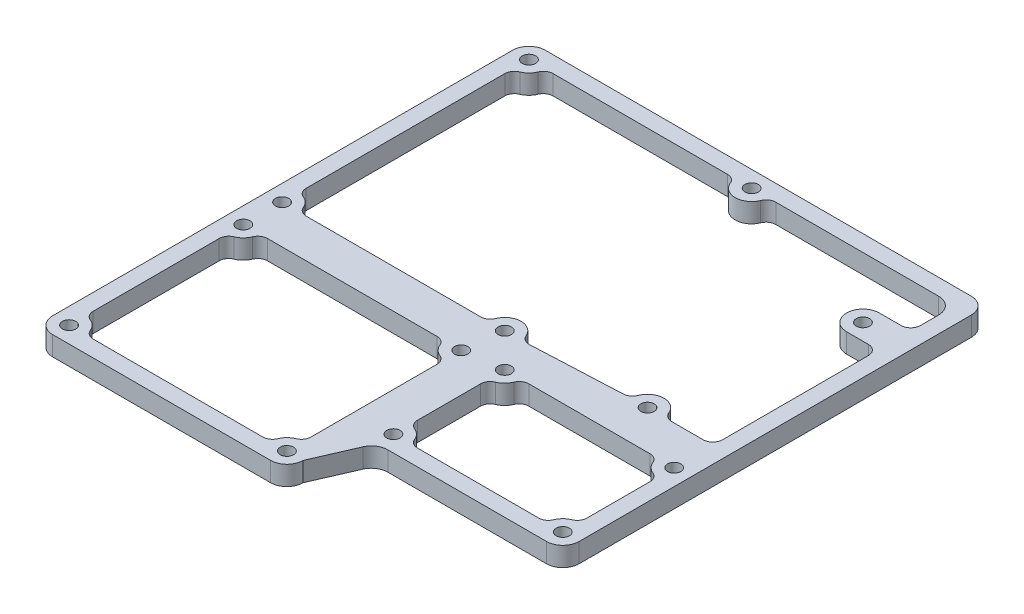
SolidWorks part; units mm, degrees
ref_plane "Front Plane" through (0, 0, 0) normal (0, 0, 1) x (1, 0, 0)
ref_plane "Top Plane" through (0, 0, 0) normal (0, 1, 0) x (1, 0, 0)
ref_plane "Right Plane" through (0, 0, 0) normal (1, 0, 0) x (0, 0, -1)
sketch "Sketch2" plane through (0, 0, 0) normal (0, 1, 0) x (1, 0, 0)
  line L1 (-46, 51) -> (0, 51) construction
  line L2 (-46, 51) -> (-46, 0) construction
  line L3 (-46, 0) -> (0, 0) construction
  line L4 (0, 51) -> (0, 0) construction
  line L5 (-46, -8) -> (-1, -8) construction
  line L6 (-46, -8) -> (-46, -44) construction
  line L7 (-46, -44) -> (-1, -44) construction
  line L8 (-1, -8) -> (-1, -44) construction
  line L9 (6, 52) -> (44, 52) construction
  line L10 (6, 52) -> (6, -2) construction
  line L11 (6, -2) -> (44, -2) construction
  line L12 (44, 52) -> (44, -2) construction
  line L13 (7, -7) -> (42, -7) construction
  line L14 (7, -7) -> (7, -30) construction
  line L15 (7, -30) -> (42, -30) construction
  line L16 (42, -7) -> (42, -30) construction
  circle A0 centre (-46, 51) radius 1.375
  circle A1 centre (0, 51) radius 1.375
  circle A2 centre (0, 0) radius 1.375
  circle A3 centre (-46, 0) radius 1.375
  circle A4 centre (-46, -8) radius 1.375
  circle A5 centre (-1, -8) radius 1.375
  circle A6 centre (-1, -44) radius 1.375
  circle A7 centre (-46, -44) radius 1.375
  circle A8 centre (28.5, 1) radius 1.375
  circle A9 centre (35.5, 38.5) radius 1.375
  circle A10 centre (7, -7) radius 1.375
  circle A11 centre (42, -7) radius 1.375
  circle A12 centre (42, -30) radius 1.375
  circle A13 centre (7, -30) radius 1.375
  circle A14 centre (-46, 51) radius 3.375
  circle A15 centre (0, 51) radius 3.375
  circle A16 centre (0, 0) radius 3.375
  circle A17 centre (-46, 0) radius 3.375
  circle A18 centre (-46, -8) radius 3.375
  circle A19 centre (-1, -8) radius 3.375
  circle A20 centre (7, -7) radius 3.375
  circle A21 centre (28.5, 1) radius 3.375
  circle A22 centre (35.5, 38.5) radius 3.375
  circle A23 centre (-1, -44) radius 3.375
  circle A24 centre (-46, -44) radius 3.375
  circle A25 centre (7, -30) radius 3.375
  circle A26 centre (42, -30) radius 3.375
  circle A27 centre (42, -7) radius 3.375
  point P33 (7.6139, -7)
  dimension "D3" = 2.75
  dimension "D4" = 45
  dimension "D9" = 3
  dimension "D17" = 5
  dimension "D1" = 46
  dimension "D2" = 51
  dimension "D5" = 36
  dimension "D6" = 8
  dimension "D7" = 38
  dimension "D8" = 54
  dimension "D10" = 15.5
  dimension "D11" = 13.5
  dimension "D12" = 8.5
  dimension "D13" = 2
  dimension "D14" = 6
  dimension "D15" = 35
  dimension "D16" = 23
  dimension "D18" = 2
  dimension "D19" = 2
extrude "Part screwholes" add sketch "Sketch2" along normal blind 4
sketch "Sketch3" plane through (0, 4, 0) normal (0, 1, 0) x (1, 0, 0)
  line L0 (-49.375, 51) -> (-49.375, -44)
  line L1 (-46, -47.375) -> (-1, -47.375)
  line L2 (2.375, -44) -> (6.1172, -35.403)
  line L3 (9.2118, -33.375) -> (42, -33.375)
  line L4 (45.375, -30) -> (45.375, 51)
  line L5 (-46, 54.375) -> (42, 54.375)
  line L6 (-46, 47.625) -> (-46, 3.375)
  line L7 (-46, -11.375) -> (-46, -40.625)
  line L8 (-42.625, -44) -> (-4.375, -44)
  line L9 (35.5, 41.875) -> (42, 41.875)
  line L10 (10.375, -30) -> (38.625, -30)
  line L11 (42, -26.625) -> (42, -10.375)
  line L12 (42, 1) -> (42, 35.125)
  line L13 (38.625, 51) -> (3.375, 51)
  line L14 (-3.375, 51) -> (-42.625, 51)
  line L15 (-42.625, 0) -> (-3.375, 0)
  line L16 (-42.625, -8) -> (-4.375, -8)
  line L17 (7, -10.375) -> (7, -26.625)
  line L18 (3.375, 0) -> (25.125, 1)
  line L19 (10.375, -7) -> (38.625, -7)
  line L20 (31.875, 1) -> (42, 1)
  line L21 (-1, -11.375) -> (-1, -40.625)
  line L22 (35.5, 35.125) -> (42, 35.125)
  line L23 (42, 41.875) -> (42, 47.625)
  circle A0 centre (-46, 51) radius 3.375 construction
  circle A1 centre (-46, -44) radius 3.375 construction
  circle A2 centre (-1, -44) radius 3.375 construction
  circle A3 centre (7, -30) radius 3.375 construction
  circle A4 centre (42, -30) radius 3.375 construction
  circle A5 centre (-46, 0) radius 3.375 construction
  circle A6 centre (-46, -8) radius 3.375 construction
  circle A7 centre (42, -7) radius 3.375 construction
  circle A8 centre (0, 51) radius 3.375 construction
  circle A9 centre (0, 0) radius 3.375 construction
  circle A10 centre (-1, -8) radius 3.375 construction
  circle A11 centre (7, -7) radius 3.375 construction
  circle A12 centre (28.5, 1) radius 3.375 construction
  circle A13 centre (35.5, 38.5) radius 3.375 construction
  circle A14 centre (35.5, 38.5) radius 1.375 construction
  circle A15 centre (0, 51) radius 1.375 construction
  circle A16 centre (-46, 51) radius 1.375 construction
  circle A17 centre (-46, 0) radius 1.375 construction
  circle A18 centre (-46, -8) radius 1.375 construction
  circle A19 centre (0, 0) radius 1.375 construction
  circle A20 centre (-1, -8) radius 1.375 construction
  circle A21 centre (7, -7) radius 1.375 construction
  circle A22 centre (28.5, 1) radius 1.375 construction
  circle A23 centre (42, -7) radius 1.375 construction
  circle A24 centre (42, -30) radius 1.375 construction
  circle A25 centre (7, -30) radius 1.375 construction
  circle A26 centre (-46, -44) radius 1.375 construction
  circle A27 centre (-1, -44) radius 1.375 construction
  circle A28 centre (35.5, 38.5) radius 1.375
  circle A29 centre (0, 51) radius 1.375
  circle A30 centre (-46, 51) radius 1.375
  circle A31 centre (-46, 0) radius 1.375
  circle A32 centre (-46, -8) radius 1.375
  circle A33 centre (0, 0) radius 1.375
  circle A34 centre (-1, -8) radius 1.375
  circle A35 centre (7, -7) radius 1.375
  circle A36 centre (28.5, 1) radius 1.375
  circle A37 centre (42, -7) radius 1.375
  circle A38 centre (42, -30) radius 1.375
  circle A39 centre (7, -30) radius 1.375
  circle A40 centre (-46, -44) radius 1.375
  circle A41 centre (-1, -44) radius 1.375
  arc A42 (-46, 47.625) -> (-42.625, 51) centre (-46, 51) ccw
  arc A43 (-3.375, 51) -> (3.375, 51) centre (0, 51) ccw
  arc A44 (35.5, 41.875) -> (35.5, 35.125) centre (35.5, 38.5) ccw
  arc A45 (42, -26.625) -> (38.625, -30) centre (42, -30) ccw
  arc A46 (38.625, -7) -> (42, -10.375) centre (42, -7) ccw
  arc A47 (31.875, 1) -> (25.125, 1) centre (28.5, 1) ccw
  arc A48 (7, -10.375) -> (10.375, -7) centre (7, -7) ccw
  arc A49 (3.375, 0) -> (-3.375, 0) centre (0, 0) ccw
  arc A50 (-4.375, -8) -> (-1, -11.375) centre (-1, -8) ccw
  arc A51 (10.375, -30) -> (7, -26.625) centre (7, -30) ccw
  arc A52 (-42.625, 0) -> (-46, 3.375) centre (-46, 0) ccw
  arc A53 (-46, -11.375) -> (-42.625, -8) centre (-46, -8) ccw
  arc A54 (-42.625, -44) -> (-46, -40.625) centre (-46, -44) ccw
  arc A55 (-1, -47.375) -> (2.375, -44) centre (-1, -44) ccw
  arc A56 (-46, 54.375) -> (-49.375, 51) centre (-46, 51) ccw
  arc A57 (-49.375, -44) -> (-46, -47.375) centre (-46, -44) ccw
  arc A58 (-1, -40.625) -> (-4.375, -44) centre (-1, -44) ccw
  arc A59 (42, -33.375) -> (45.375, -30) centre (42, -30) ccw
  arc A60 (6.1172, -35.403) -> (9.2118, -33.375) centre (9.2118, -36.75) cw
  arc A61 (42, 47.625) -> (38.625, 51) centre (38.625, 47.625) ccw
  arc A62 (42, 54.375) -> (45.375, 51) centre (42, 51) cw
  point P119 (0, 0)
  point P120 (0, 0)
  point P121 (0, 0)
  point P122 (0, 0)
  point P123 (0, 0)
  point P124 (0, 0)
  point P125 (0, 0)
  point P126 (0, 0)
  point P127 (0, 0)
  point P128 (0, 0)
  point P129 (0, 0)
  point P130 (0, 0)
  point P133 (7, -33.375)
  dimension "D1" = 3.375
extrude "Frame" add sketch "Sketch3" against normal blind 4
fillet "General rounding 2mm" radius 2 29 edges at (-42.625, 2, 8) (-46, 2, 11.375) (-42.625, 2, 44) (-46, 2, 40.625) (10.375, 2, 30) (7, 2, 26.625) (-1, 2, 40.625) (-4.375, 2, 44) (38.625, 2, 30) (42, 2, 26.625) (42, 2, 10.375) (38.625, 2, 7) (10.375, 2, 7) (7, 2, 10.375) (-4.375, 2, 8) (-1, 2, 11.375) (42, 2, -35.125) (42, 2, -41.875) (42, 2, -1) (25.125, 2, -1) (31.875, 2, -1) (-3.375, 2, 0) (3.375, 2, 0) (-42.625, 2, 0) (-46, 2, -3.375) (-3.375, 2, -51) (3.375, 2, -51) (-46, 2, -47.625) (-42.625, 2, -51)
